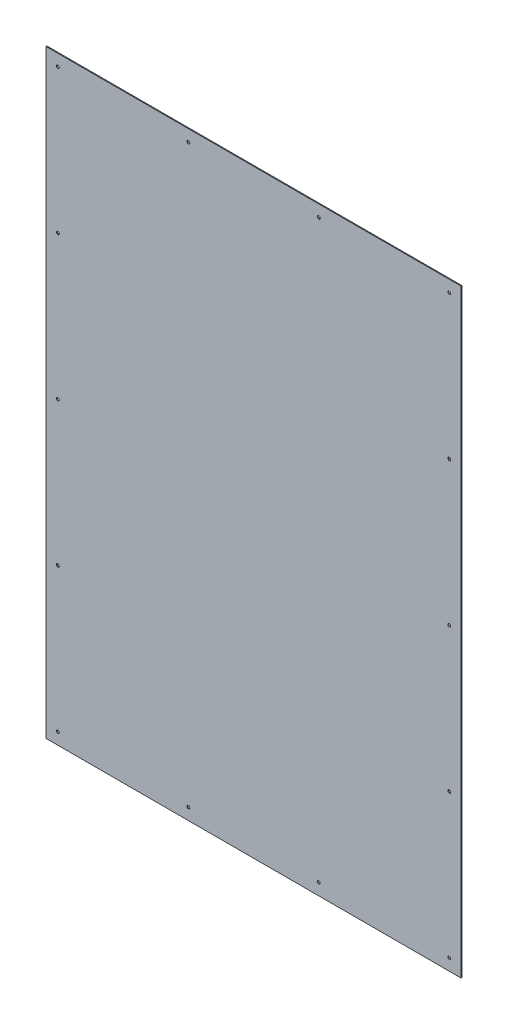
SolidWorks part; units mm, degrees
ref_plane "Alzado" through (0, 0, 0) normal (0, 0, 1) x (1, 0, 0)
ref_plane "Planta" through (0, 0, 0) normal (0, 1, 0) x (1, 0, 0)
ref_plane "Vista lateral" through (0, 0, 0) normal (1, 0, 0) x (0, 0, -1)
sketch "Croquis1" plane through (0, 0, 0) normal (0, 0, 1) x (1, 0, 0)
  line L1 (-450, 650) -> (450, 650)
  line L2 (-450, 650) -> (-450, -650)
  line L3 (-450, -650) -> (450, -650)
  line L4 (450, 650) -> (450, -650)
  line L5 (-450, 650) -> (450, -650) construction
  line L6 (-450, -650) -> (450, 650) construction
  point P0 (0, 0)
  dimension "D1" = 900
  dimension "D2" = 1300
extrude "Saliente-Extruir1" add sketch "Croquis1" along normal blind 1.9
sketch "Croquis2" plane through (0, 0, 1.9) normal (0, 0, 1) x (1, 0, 0)
  line L0 (450, 650) -> (-450, 650) construction
  line L1 (-424.6, 624.6) -> (424.6, 624.6) construction
  line L2 (-424.6, 624.6) -> (-424.6, -624.6) construction
  line L3 (-424.6, -624.6) -> (424.6, -624.6) construction
  line L4 (424.6, 624.6) -> (424.6, -624.6) construction
  line L5 (-424.6, 624.6) -> (424.6, -624.6) construction
  line L6 (-424.6, -624.6) -> (424.6, 624.6) construction
  line L7 (450, -650) -> (450, 650) construction
  line L8 (0, 0) -> (424.6, 0) construction
  line L9 (0, 0) -> (0, -624.6) construction
  line L10 (424.6, 624.6) -> (141.54, 624.6) construction
  line L11 (141.54, 624.6) -> (-141.52, 624.6) construction
  line L12 (0, 0) -> (-424.6, 0) construction
  line L13 (424.6, 624.6) -> (424.6, 0) construction
  line L14 (424.6, 0) -> (424.6, 312.3) construction
  line L15 (424.6, -624.6) -> (424.6, 0) construction
  line L16 (424.6, 0) -> (424.6, -312.3) construction
  circle A0 centre (424.6, 624.6) radius 3.175
  circle A1 centre (424.6, -624.6) radius 3.175
  circle A2 centre (-424.6, -624.6) radius 3.175
  circle A3 centre (-424.6, 624.6) radius 3.175
  circle A4 centre (141.54, 624.6) radius 3.175
  circle A5 centre (-141.52, 624.6) radius 3.175
  circle A6 centre (-141.52, -624.6) radius 3.175
  circle A7 centre (141.54, -624.6) radius 3.175
  circle A8 centre (424.6, 0) radius 3.175
  circle A9 centre (424.6, 312.3) radius 3.175
  circle A10 centre (424.6, -312.3) radius 3.175
  circle A11 centre (-424.6, -312.3) radius 3.175
  circle A12 centre (-424.6, 0) radius 3.175
  circle A13 centre (-424.6, 312.3) radius 3.175
  point P0 (0, 0)
  dimension "D3" = 6.35
  dimension "D6" = 6.35
  dimension "D7" = 6.35
  dimension "D8" = 6.35
  dimension "D9" = 6.35
  dimension "D10" = 6.35
  dimension "D1" = 25.4
  dimension "D2" = 25.4
  dimension "D4" = 283.06
  dimension "D5" = 283.06
extrude "Cortar-Extruir1" cut sketch "Croquis2" against normal blind 10
